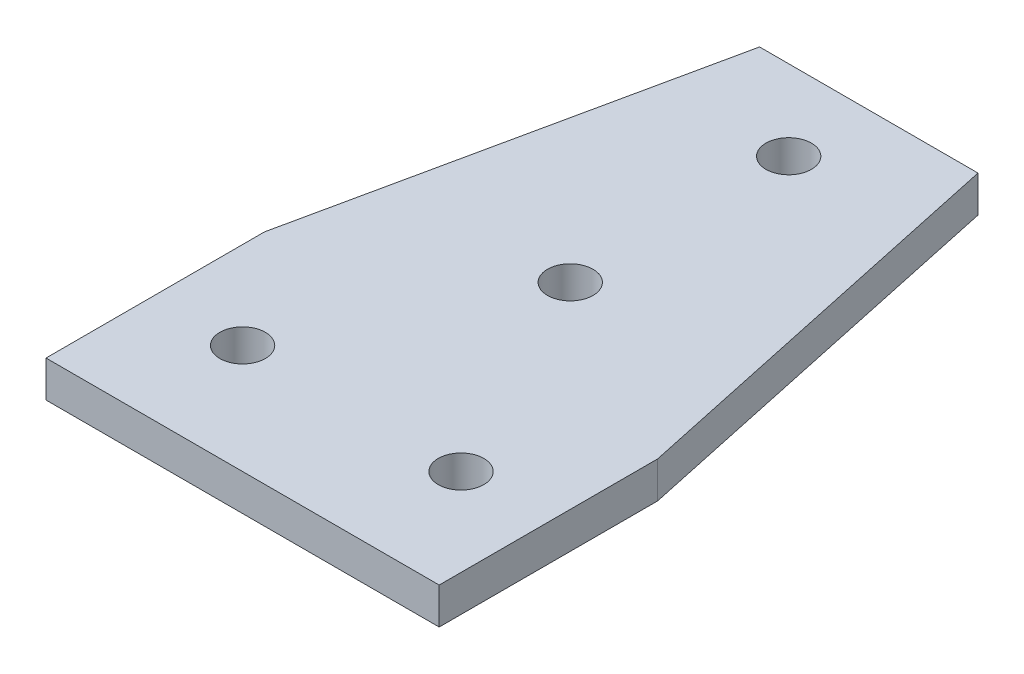
SolidWorks part; units mm, degrees
ref_plane "Front Plane" through (0, 0, 0) normal (0, 0, 1) x (1, 0, 0)
ref_plane "Top Plane" through (0, 0, 0) normal (0, 1, 0) x (1, 0, 0)
ref_plane "Right Plane" through (0, 0, 0) normal (1, 0, 0) x (0, 0, -1)
sketch "Sketch1" plane through (0, 0, 0) normal (0, 1, 0) x (1, 0, 0)
  line L0 (-19.05, 0) -> (19.05, 0) construction
  line L1 (0, 0) -> (0, 76.2) construction
  line L2 (-34.29, 19.05) -> (-34.29, -19.05)
  line L3 (-34.29, -19.05) -> (34.29, -19.05)
  line L4 (34.29, -19.05) -> (34.29, 19.05)
  line L5 (-34.29, 0) -> (-19.05, 0) construction
  line L6 (-19.05, 90.17) -> (19.05, 90.17)
  line L7 (0, 90.17) -> (0, 76.2) construction
  line L8 (-34.29, 19.05) -> (-19.05, 90.17)
  line L9 (19.05, 90.17) -> (34.29, 19.05)
  circle A0 centre (-19.05, 0) radius 3.9688
  circle A1 centre (19.05, 0) radius 3.9687
  circle A2 centre (0, 76.2) radius 3.9687
  circle A3 centre (0, 38.1) radius 3.9687
  dimension "D1" = 7.9375
  dimension "D2" = 38.1
  dimension "D3" = 76.2
  dimension "D4" = 38.1
  dimension "D5" = 15.24
  dimension "D6" = 15.24
  dimension "D7" = 38.1
  dimension "D8" = 13.97
extrude "Boss-Extrude1" add sketch "Sketch1" along normal blind 6.35
